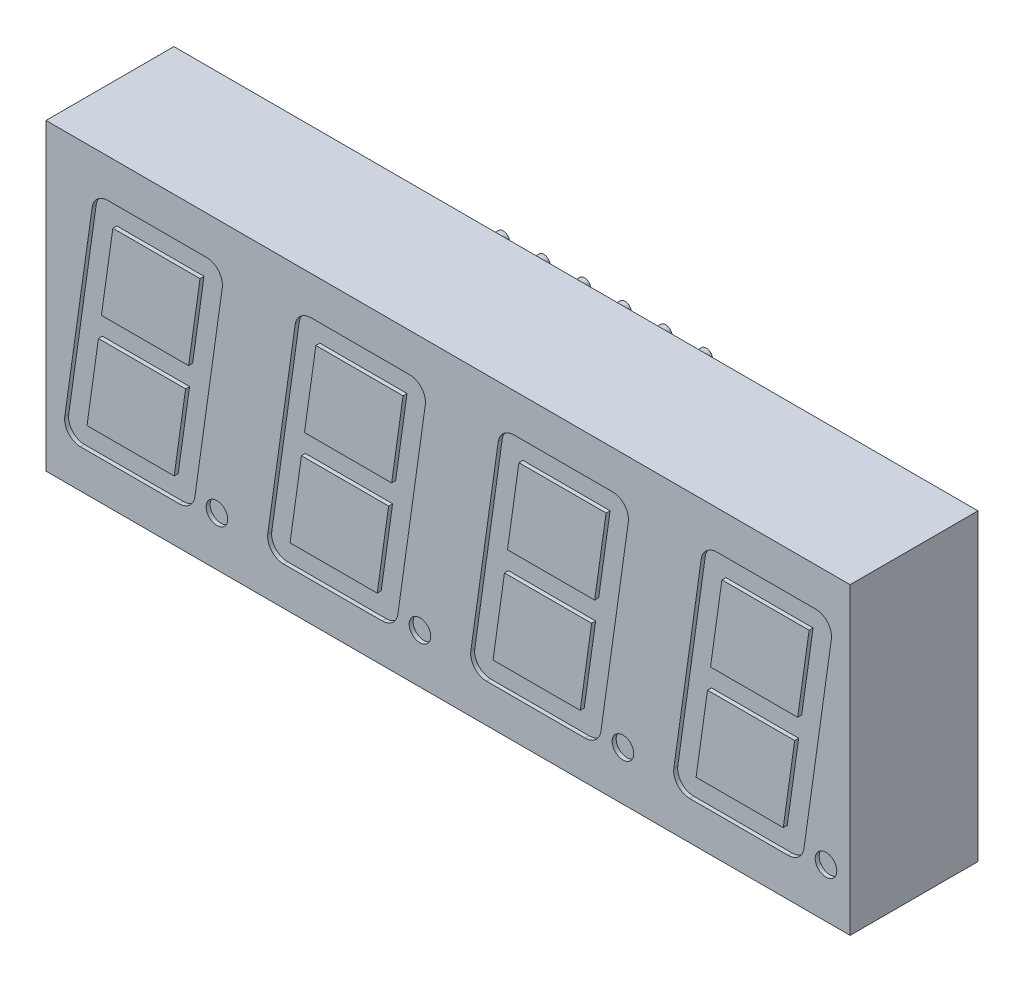
SolidWorks part; units mm, degrees
ref_plane "前视基准面" through (0, 0, 0) normal (0, 0, 1) x (1, 0, 0)
ref_plane "上视基准面" through (0, 0, 0) normal (0, 1, 0) x (1, 0, 0)
ref_plane "右视基准面" through (0, 0, 0) normal (1, 0, 0) x (0, 0, -1)
sketch "草图1" plane through (0, 0, 0) normal (0, 0, 1) x (1, 0, 0)
  line L1 (0, 0) -> (50.3, 0)
  line L2 (0, 0) -> (0, 19)
  line L3 (0, 19) -> (50.3, 19)
  line L4 (50.3, 0) -> (50.3, 19)
  dimension "D1" = 50.3
  dimension "D2" = 19
extrude "凸台-拉伸1" add sketch "草图1" along normal blind 8
sketch "草图2" plane through (0, 0, 0) normal (0, 0, -1) x (-1, 0, 0)
  line L0 (-50.3, 9.5) -> (0, 9.5) construction
  line L1 (-50.3, 0) -> (-50.3, 19) construction
  line L2 (0, 19) -> (0, 0) construction
  line L3 (-25.15, 19) -> (-25.15, 0) construction
  line L4 (-50.3, 19) -> (0, 19) construction
  line L5 (0, 0) -> (-50.3, 0) construction
  circle A0 centre (-31.5, 17.12) radius 0.4
  circle A1 centre (-28.96, 17.12) radius 0.4
  circle A2 centre (-26.42, 17.12) radius 0.4
  circle A3 centre (-23.88, 17.12) radius 0.4
  circle A4 centre (-21.34, 17.12) radius 0.4
  circle A5 centre (-18.8, 17.12) radius 0.4
  circle A6 centre (-18.8, 1.88) radius 0.4
  circle A7 centre (-21.34, 1.88) radius 0.4
  circle A8 centre (-23.88, 1.88) radius 0.4
  circle A9 centre (-26.42, 1.88) radius 0.4
  circle A10 centre (-28.96, 1.88) radius 0.4
  circle A11 centre (-31.5, 1.88) radius 0.4
  dimension "D1" = 0.8
  dimension "D2" = 12.7
  dimension "D3" = 15.24
  dimension "D4" = 6
extrude "凸台-拉伸2" add sketch "草图2" along normal blind 1.8
sketch "草图3" plane through (0, 0, 8) normal (0, 0, 1) x (1, 0, 0)
  line L0 (25.15, 19) -> (25.15, 0) construction
  line L1 (50.3, 19) -> (0, 19) construction
  line L2 (0, 0) -> (50.3, 0) construction
  line L3 (11.0275, 15.4608) -> (9.3129, 3.2608)
  line L4 (44.2, 19) -> (44.2, 0) construction
  line L5 (31.5, 19) -> (31.5, 0) construction
  line L6 (18.8, 19) -> (18.8, 0) construction
  line L7 (6.1, 19) -> (6.1, 0) construction
  line L8 (0, 9.5) -> (50.3, 9.5) construction
  line L9 (0, 19) -> (0, 0) construction
  line L10 (50.3, 0) -> (50.3, 19) construction
  line L11 (3.8773, 16.6) -> (10.0373, 16.6)
  line L12 (2.1627, 2.4) -> (8.3227, 2.4)
  line L13 (6.1, 9.5) -> (7.8499, 21.9509) construction
  line L14 (2.8871, 15.7392) -> (1.1725, 3.5392)
  line L15 (3.2786, 8.825) -> (2.5654, 3.75)
  line L16 (2.5654, 3.75) -> (8.0184, 3.75)
  line L17 (4.1816, 15.25) -> (9.6346, 15.25)
  line L18 (9.8254, 16.6073) -> (9.8244, 16.6)
  line L19 (4.1816, 15.25) -> (3.4683, 10.175)
  line L20 (8.7317, 8.825) -> (8.0184, 3.75)
  line L21 (9.6346, 15.25) -> (8.9214, 10.175)
  line L22 (15.5871, 15.7392) -> (13.8725, 3.5392)
  line L23 (3.4683, 10.175) -> (8.9214, 10.175)
  line L24 (3.2786, 8.825) -> (8.7317, 8.825)
  line L25 (16.8816, 15.25) -> (16.1683, 10.175)
  line L26 (16.8816, 15.25) -> (22.3346, 15.25)
  line L27 (16.5773, 16.6) -> (22.7373, 16.6)
  line L28 (22.3346, 15.25) -> (21.6214, 10.175)
  line L29 (23.7275, 15.4608) -> (22.0129, 3.2608)
  line L30 (21.4317, 8.825) -> (20.7184, 3.75)
  line L31 (15.9786, 8.825) -> (15.2654, 3.75)
  line L32 (15.9786, 8.825) -> (21.4317, 8.825)
  line L33 (15.2654, 3.75) -> (20.7184, 3.75)
  line L34 (14.8627, 2.4) -> (21.0227, 2.4)
  line L35 (16.1683, 10.175) -> (21.6214, 10.175)
  line L36 (28.2871, 15.7392) -> (26.5725, 3.5392)
  line L37 (29.5816, 15.25) -> (28.8683, 10.175)
  line L38 (29.5816, 15.25) -> (35.0346, 15.25)
  line L39 (29.2773, 16.6) -> (35.4373, 16.6)
  line L40 (35.0346, 15.25) -> (34.3214, 10.175)
  line L41 (36.4275, 15.4608) -> (34.7129, 3.2608)
  line L42 (34.1317, 8.825) -> (33.4184, 3.75)
  line L43 (28.6786, 8.825) -> (27.9654, 3.75)
  line L44 (28.6786, 8.825) -> (34.1317, 8.825)
  line L45 (27.9654, 3.75) -> (33.4184, 3.75)
  line L46 (27.5627, 2.4) -> (33.7227, 2.4)
  line L47 (28.8683, 10.175) -> (34.3214, 10.175)
  line L48 (40.9871, 15.7392) -> (39.2725, 3.5392)
  line L49 (42.2816, 15.25) -> (41.5683, 10.175)
  line L50 (42.2816, 15.25) -> (47.7346, 15.25)
  line L51 (41.9773, 16.6) -> (48.1373, 16.6)
  line L52 (47.7346, 15.25) -> (47.0214, 10.175)
  line L53 (49.1275, 15.4608) -> (47.4129, 3.2608)
  line L54 (46.8317, 8.825) -> (46.1184, 3.75)
  line L55 (41.3786, 8.825) -> (40.6654, 3.75)
  line L56 (41.3786, 8.825) -> (46.8317, 8.825)
  line L57 (40.6654, 3.75) -> (46.1184, 3.75)
  line L58 (40.2627, 2.4) -> (46.4227, 2.4)
  line L59 (41.5683, 10.175) -> (47.0214, 10.175)
  circle A0 centre (10.692, 3.075) radius 0.675
  arc A1 (11.0275, 15.4608) -> (10.0373, 16.6) centre (10.0373, 15.6) ccw
  arc A2 (2.8871, 15.7392) -> (3.8773, 16.6) centre (3.8773, 15.6) cw
  arc A3 (2.1627, 2.4) -> (1.1725, 3.5392) centre (2.1627, 3.4) cw
  arc A4 (9.3129, 3.2608) -> (8.3227, 2.4) centre (8.3227, 3.4) cw
  arc A5 (14.8627, 2.4) -> (13.8725, 3.5392) centre (14.8627, 3.4) cw
  arc A6 (22.0129, 3.2608) -> (21.0227, 2.4) centre (21.0227, 3.4) cw
  arc A7 (15.5871, 15.7392) -> (16.5773, 16.6) centre (16.5773, 15.6) cw
  arc A8 (23.7275, 15.4608) -> (22.7373, 16.6) centre (22.7373, 15.6) ccw
  arc A9 (27.5627, 2.4) -> (26.5725, 3.5392) centre (27.5627, 3.4) cw
  arc A10 (34.7129, 3.2608) -> (33.7227, 2.4) centre (33.7227, 3.4) cw
  arc A11 (28.2871, 15.7392) -> (29.2773, 16.6) centre (29.2773, 15.6) cw
  arc A12 (36.4275, 15.4608) -> (35.4373, 16.6) centre (35.4373, 15.6) ccw
  arc A13 (40.2627, 2.4) -> (39.2725, 3.5392) centre (40.2627, 3.4) cw
  arc A14 (47.4129, 3.2608) -> (46.4227, 2.4) centre (46.4227, 3.4) cw
  arc A15 (40.9871, 15.7392) -> (41.9773, 16.6) centre (41.9773, 15.6) cw
  arc A16 (49.1275, 15.4608) -> (48.1373, 16.6) centre (48.1373, 15.6) ccw
  circle A17 centre (23.392, 3.075) radius 0.675
  circle A18 centre (36.092, 3.075) radius 0.675
  circle A19 centre (48.792, 3.075) radius 0.675
  point P46 (9.192, 2.4)
  dimension "D6" = 1.35
  dimension "D8" = 1.5
  dimension "D9" = 1
  dimension "D10" = 1
  dimension "D11" = 1
  dimension "D12" = 1
  dimension "D1" = 19.05
  dimension "D2" = 4
  dimension "D3" = 14.2
  dimension "D5" = 8.1
  dimension "D7" = 1.35
  dimension "D13" = 4
  dimension "D14" = 4
extrude "切除-拉伸1" cut sketch "草图3" against normal blind 0.25 contours A4 L3 A1 L11 A2 L14 A3 L12 L23 L19 L17 L21 L15 L24 L20 L16 | L29 A8 L27 A7 L22 A5 L34 A6 L35 L25 L26 L28 L33 L31 L32 L30 | L41 A12 L39 A11 L36 A9 L46 A10 L47 L37 L38 L40 L45 L43 L44 L42 | L53 A16 L51 A15 L48 A13 L58 A14 L59 L49 L50 L52 L57 L55 L56 L54 | A0 | A17 | A18 | A19
